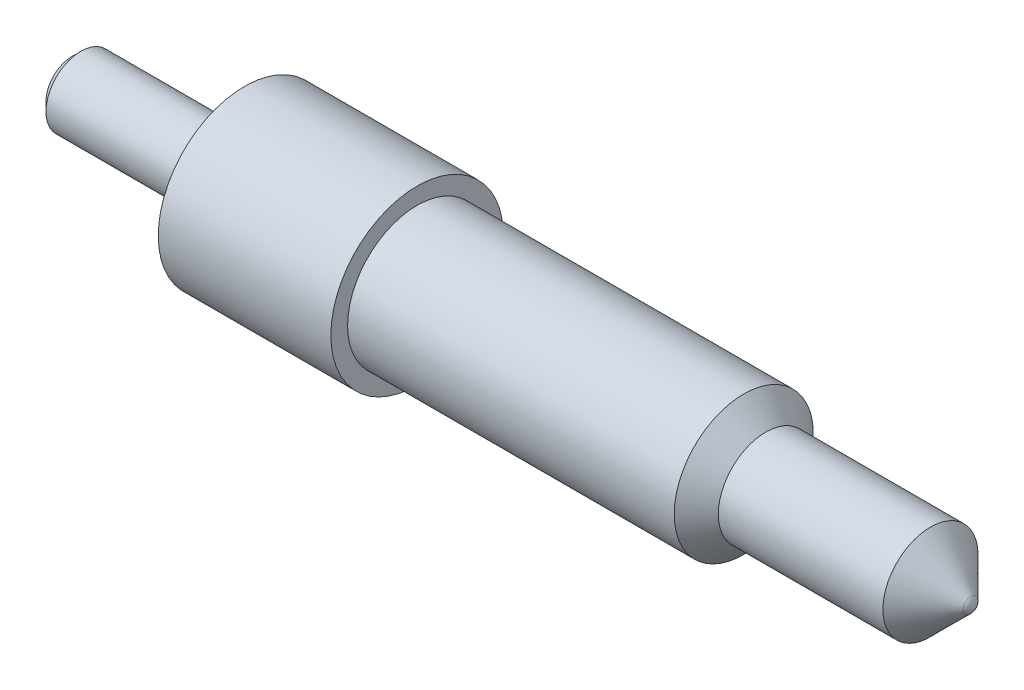
SolidWorks part; units mm, degrees
ref_plane "Front Plane" through (0, 0, 0) normal (0, 0, 1) x (1, 0, 0)
ref_plane "Top Plane" through (0, 0, 0) normal (0, 1, 0) x (1, 0, 0)
ref_plane "Right Plane" through (0, 0, 0) normal (1, 0, 0) x (0, 0, -1)
sketch "Sketch1" plane through (0, 0, 0) normal (0, 0, 1) x (1, 0, 0)
  line L0 (-3.4479, 0) -> (21.9521, 0) construction
  line L1 (0, 0) -> (0, 0.3746)
  line L2 (0, 0.3746) -> (0.127, 0.5016)
  line L3 (0.127, 0.5016) -> (2.4892, 0.5016)
  line L4 (2.4892, 0.5016) -> (2.4892, 1.2446)
  line L5 (2.4892, 1.2446) -> (4.9784, 1.2446)
  line L6 (4.9784, 1.2446) -> (4.9784, 1.0033)
  line L7 (4.9784, 1.0033) -> (9.6901, 1.0033)
  line L8 (9.6901, 1.0033) -> (10.0076, 0.6858)
  line L9 (10.0076, 0.6858) -> (12.3821, 0.6858)
  line L10 (12.3821, 0.6858) -> (12.9602, 0.1078)
  line L11 (13.0048, 0) -> (0, 0)
  arc A0 (13.0048, 0) -> (12.9602, 0.1078) centre (12.8524, 0) ccw
  dimension "D7" = 0.3048
  dimension "D1" = 45
  dimension "D2" = 1.0033
  dimension "D3" = 0.127
  dimension "D4" = 2.4892
  dimension "D5" = 2.0066
  dimension "D6" = 1.3716
  dimension "D8" = 13.0048
  dimension "D9" = 2.9972
  dimension "D10" = 2.4892
  dimension "D11" = 2.4892
revolve "Revolve1" add sketch "Sketch1" angle 360 about L0
